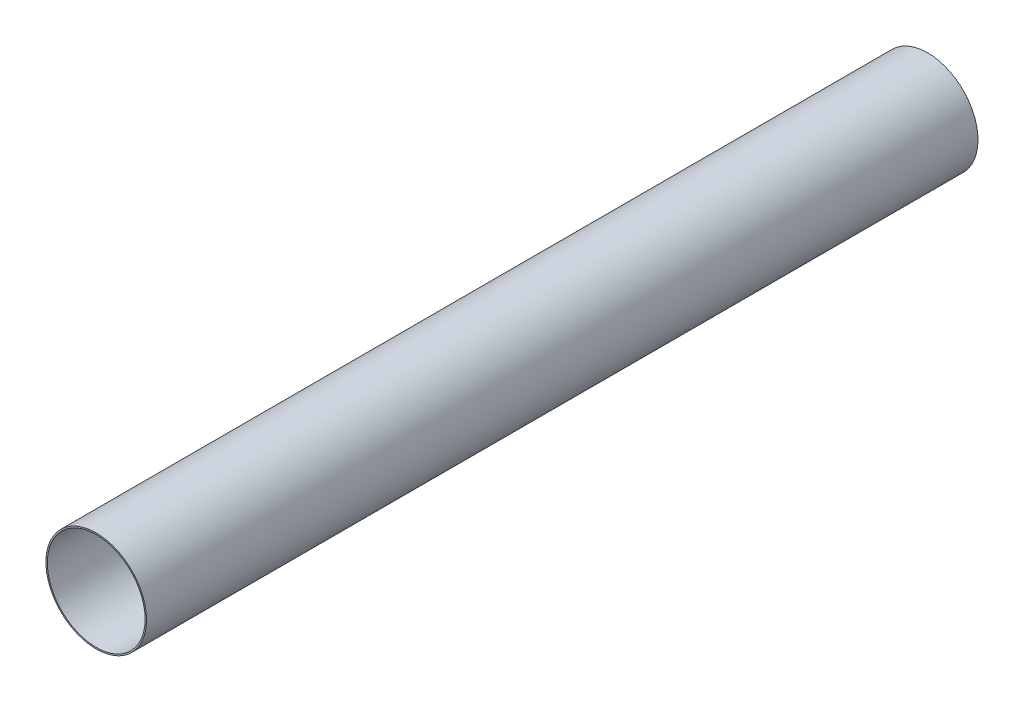
SolidWorks part; units mm, degrees
ref_plane "Front Plane" through (0, 0, 0) normal (0, 0, 1) x (1, 0, 0)
ref_plane "Top Plane" through (0, 0, 0) normal (0, 1, 0) x (1, 0, 0)
ref_plane "Right Plane" through (0, 0, 0) normal (1, 0, 0) x (0, 0, -1)
sketch "Sketch1" plane through (0, 0, 0) normal (0, 0, 1) x (1, 0, 0)
  circle A0 centre (0, 0) radius 78.359
  circle A1 centre (0, 0) radius 76.2
  dimension "D1" = 156.718
  dimension "D2" = 152.4
extrude "Boss-Extrude1" add sketch "Sketch1" along normal blind 1295.4
